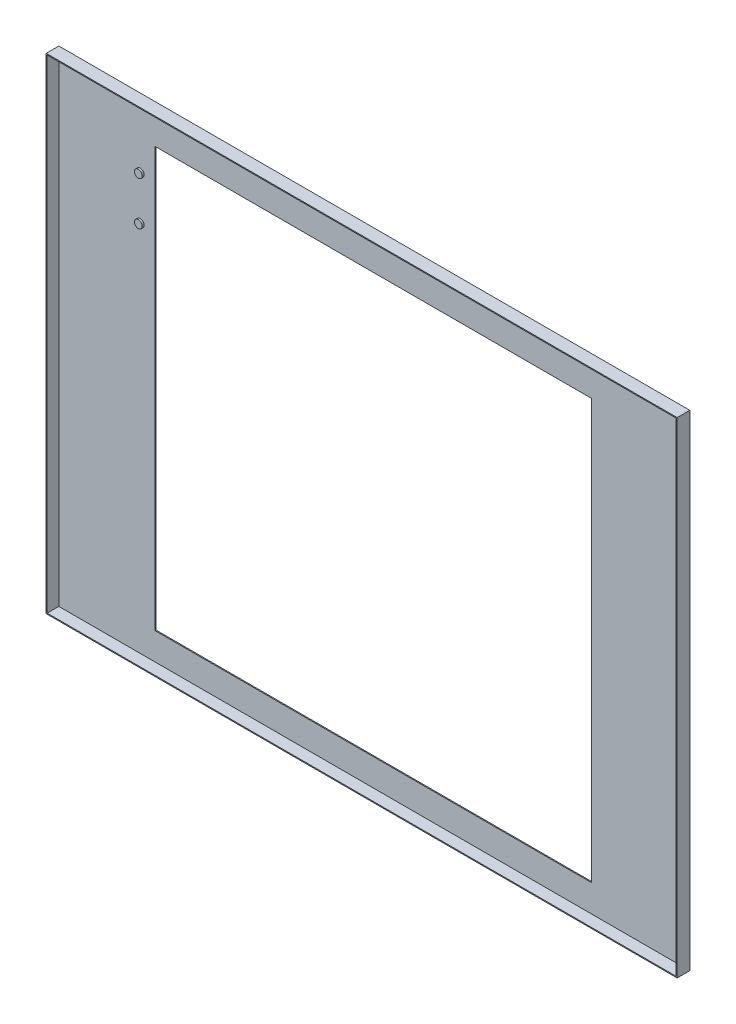
SolidWorks part; units mm, degrees
ref_plane "Front Plane" through (0, 0, 0) normal (0, 0, 1) x (1, 0, 0)
ref_plane "Top Plane" through (0, 0, 0) normal (0, 1, 0) x (1, 0, 0)
ref_plane "Right Plane" through (0, 0, 0) normal (1, 0, 0) x (0, 0, -1)
sketch "Sketch1" plane through (0, 0, 0) normal (0, 0, 1) x (1, 0, 0)
  line L1 (325, -250) -> (-325, -250)
  line L2 (325, -250) -> (325, 250)
  line L3 (325, 250) -> (-325, 250)
  line L4 (-325, -250) -> (-325, 250)
  line L5 (325, -250) -> (-325, 250) construction
  line L6 (325, 250) -> (-325, -250) construction
  line L7 (225, -211) -> (-225, -211)
  line L8 (225, -211) -> (225, 211)
  line L9 (225, 211) -> (-225, 211)
  line L10 (-225, -211) -> (-225, 211)
  line L11 (225, -211) -> (-225, 211) construction
  line L12 (225, 211) -> (-225, -211) construction
  point P0 (0, 0)
  point P6 (0, 0)
  dimension "D1" = 650
  dimension "D2" = 500
  dimension "D3" = 0
  dimension "D4" = 450
  dimension "D5" = 422
extrude "Boss-Extrude1" add sketch "Sketch1" along normal blind 13
sketch "Sketch2" plane through (0, 0, 0) normal (0, 0, -1) x (-1, 0, 0)
  line L0 (225, 211) -> (225, -211) construction
  line L1 (-225, -211) -> (225, -211)
  line L2 (-225, -211) -> (-225, -221)
  line L3 (-225, -221) -> (225, -221)
  line L4 (225, -211) -> (225, -221)
  dimension "D1" = 10
extrude "Cut-Extrude1" cut sketch "Sketch2" against normal up to surface (13 mm away) up to face at (0, 0, 13)
shell "Shell1" thickness 1
sketch "Sketch3" plane through (0, 0, 1) normal (0, 0, 1) x (1, 0, 0)
  circle A0 centre (-240.1069, 180) radius 4
  dimension "D1" = 8
extrude "Boss-Extrude2" add sketch "Sketch3" along normal blind 2
pattern_linear "LPattern1" count 2 spacing 45 along (0, -1, 0) of "Boss-Extrude2"
